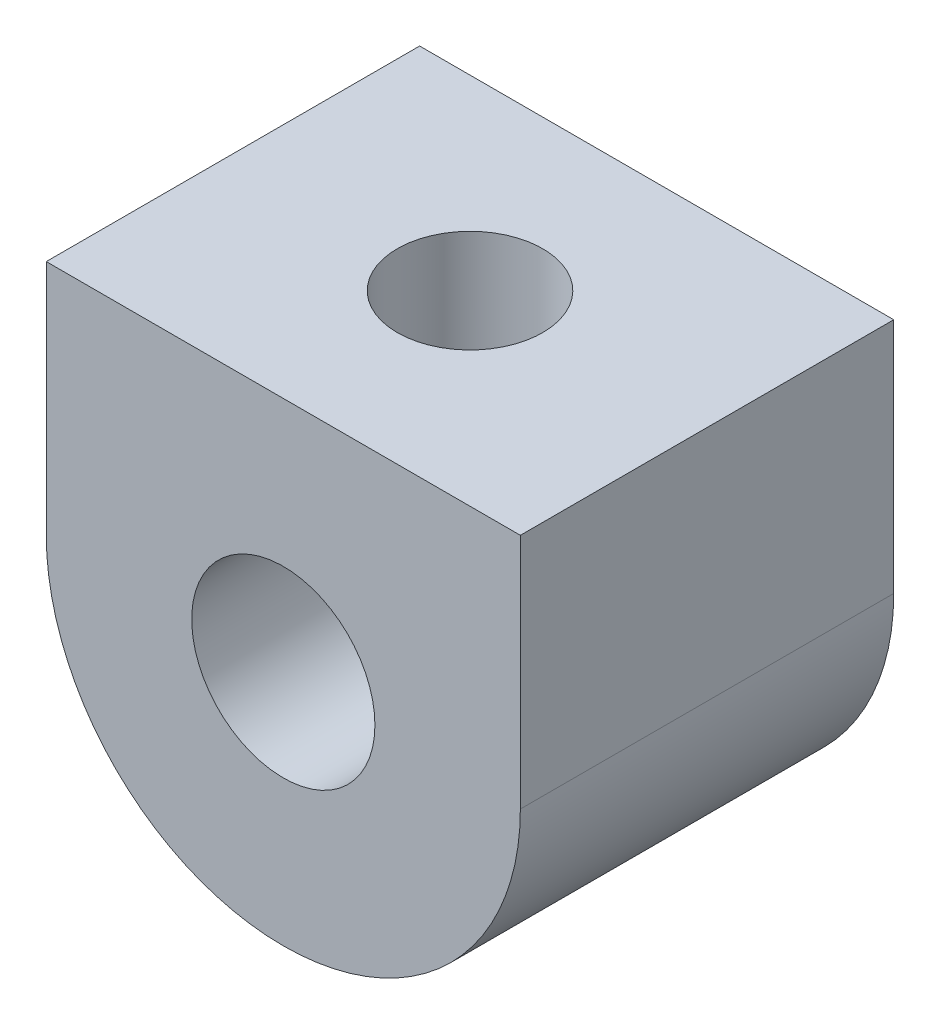
SolidWorks part; units mm, degrees
ref_plane "Front Plane" through (0, 0, 0) normal (0, 0, 1) x (1, 0, 0)
ref_plane "Top Plane" through (0, 0, 0) normal (0, 1, 0) x (1, 0, 0)
ref_plane "Right Plane" through (0, 0, 0) normal (1, 0, 0) x (0, 0, -1)
sketch "Sketch2" plane through (0, 0, 0) normal (0, 0, 1) x (1, 0, 0)
  line L0 (-10.35, 0) -> (-10.35, 10.35)
  line L1 (-10.35, 10.35) -> (0, 10.35)
  line L2 (0, 10.35) -> (10.35, 10.35)
  line L3 (10.35, 10.35) -> (10.35, 0)
  circle A0 centre (0, 0) radius 4
  arc A1 (-10.35, 0) -> (10.35, 0) centre (0, 0) ccw
  circle A2 centre (0, 0) radius 10.35 construction
  dimension "D1" = 8
  dimension "D2" = 6.35
extrude "Boss-Extrude1" add sketch "Sketch2" along normal blind 16.302
sketch "Sketch3" plane through (0, 10.35, 0) normal (0, 1, 0) x (1, 0, 0)
  line L0 (-10.35, -16.302) -> (10.35, 0) construction
  circle A0 centre (0, -8.151) radius 3.175
  point P4 (0, -8.151)
  dimension "D1" = 6.35
extrude "Cut-Extrude1" cut sketch "Sketch3" against normal up to next
